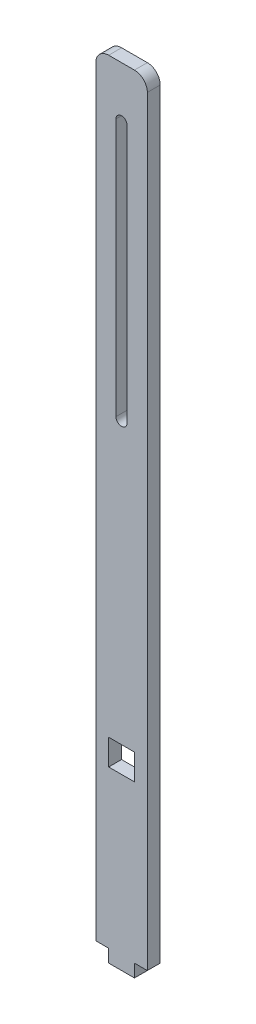
SolidWorks part; units mm, degrees
material "Pin"
ref_plane "Front" through (0, 0, 0) normal (0, 0, 1) x (1, 0, 0)
ref_plane "Top" through (0, 0, 0) normal (0, 1, 0) x (1, 0, 0)
ref_plane "Right" through (0, 0, 0) normal (1, 0, 0) x (0, 0, -1)
sketch "Esquisse2" plane through (0, 0, 0) normal (0, 0, 1) x (1, 0, 0)
  line L0 (6.35, -190.5) -> (12.7, -190.5)
  line L1 (-12.7, 190.5) -> (12.7, 190.5)
  line L2 (-12.7, 190.5) -> (-12.7, -190.5)
  line L3 (-12.7, -190.5) -> (-6.35, -190.5)
  line L4 (12.7, 190.5) -> (12.7, -190.5)
  line L5 (-12.7, 190.5) -> (12.7, -190.5) construction
  line L6 (-12.7, -190.5) -> (12.7, 190.5) construction
  line L8 (-6.35, -190.5) -> (-6.35, -196.85)
  line L9 (-6.35, -196.85) -> (6.35, -196.85)
  line L10 (6.35, -190.5) -> (6.35, -196.85)
  point P0 (0, 0)
  point P10 (-6.35, -193.675)
  dimension "D1" = 381
  dimension "D2" = 25.4
  dimension "D3" = 6.35
  dimension "D4" = 6.35
  dimension "D5" = 6.35
extrude "Boss.-Extru.1" add sketch "Esquisse2" along normal blind 6.35
sketch "Esquisse3" plane through (0, 0, 6.35) normal (0, 0, 1) x (1, 0, 0)
  line L0 (12.7, -190.5) -> (12.7, 190.5) construction
  line L1 (-6.35, -100.4748) -> (6.35, -100.4748)
  line L2 (-6.35, -100.4748) -> (-6.35, -113.1748)
  line L3 (-6.35, -113.1748) -> (6.35, -113.1748)
  line L4 (6.35, -100.4748) -> (6.35, -113.1748)
  line L5 (-6.35, -100.4748) -> (6.35, -113.1748) construction
  line L6 (-6.35, -113.1748) -> (6.35, -100.4748) construction
  line L7 (-12.7, -190.5) -> (-6.35, -190.5) construction
  point P0 (0, -106.8248)
  dimension "D1" = 12.7
  dimension "D2" = 12.7
  dimension "D3" = 6.35
  dimension "D4" = 83.6752
extrude "Enlèv. mat.-Extru.1" cut sketch "Esquisse3" against normal through all
sketch "Esquisse4" plane through (0, 0, 6.35) normal (0, 0, 1) x (1, 0, 0)
  line L0 (0, 165.1) -> (0, 38.1) construction
  line L1 (2.75, 165.1) -> (2.75, 38.1)
  line L2 (-2.75, 165.1) -> (-2.75, 38.1)
  line L3 (6.35, -190.5) -> (12.7, -190.5) construction
  arc A0 (2.75, 165.1) -> (-2.75, 165.1) centre (0, 165.1) ccw
  arc A1 (-2.75, 38.1) -> (2.75, 38.1) centre (0, 38.1) ccw
  point P3 (0, 101.6)
  dimension "D1" = 228.6
  dimension "D2" = 127
  dimension "D3" = 5.5
extrude "Enlèv. mat.-Extru.2" cut sketch "Esquisse4" against normal through all
fillet "Congé1" radius 6.35 2 edges at (-12.7, 190.5, 3.175) (12.7, 190.5, 3.175)
